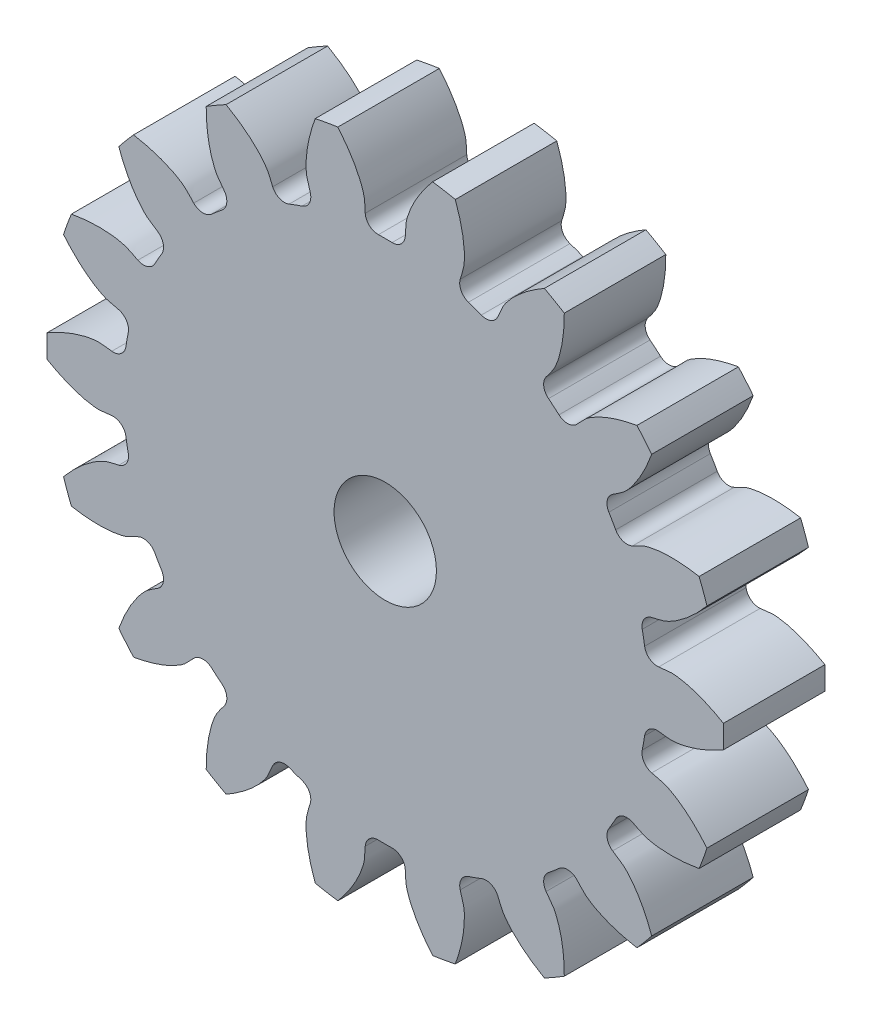
SolidWorks part; units mm, degrees
ref_plane "前视基准面" through (0, 0, 0) normal (0, 0, 1) x (1, 0, 0)
ref_plane "上视基准面" through (0, 0, 0) normal (0, 1, 0) x (1, 0, 0)
ref_plane "右视基准面" through (0, 0, 0) normal (1, 0, 0) x (0, 0, -1)
other "Configuration Table"
ref_axis "Axis1" through (0, 0, -88.99) along (0, 0, 1)
sketch "草图1" plane through (0, 0, 0) normal (0, 0, 1) x (1, 0, 0)
  circle A0 centre (0, 0) radius 20
extrude "LaShenA" add sketch "草图1" along normal blind 6
sketch "SketchA" plane through (0, 0, 6) normal (0, 0, 1) x (1, 0, 0)
  line L0 (0, 0) -> (0, 20) construction
  arc A0 (0.4048, 15.4947) -> (-0.4048, 15.4947) centre (0, 0) ccw
  arc A1 (3.8455, 20.8805) -> (-3.8455, 20.8805) centre (0, 0) ccw
  arc A2 (-0.4048, 15.4947) -> (-1.1828, 16.202) centre (-0.4246, 16.2545) cw
  arc A3 (1.1828, 16.202) -> (0.4048, 15.4947) centre (0.4246, 16.2545) cw
  circle A4 centre (0, 0) radius 16.9145 construction
  circle A5 centre (0, 0) radius 20 construction
  circle A6 centre (0, 0) radius 15.5 construction
  circle A7 centre (0, 0) radius 18 construction
  spline S0 degree 3 poles (1.1828, 16.202) (1.1983, 16.426) (1.1959, 16.7045) (1.2447, 17.0044) (1.2697, 17.1106) (1.2916, 17.1946) (1.3197, 17.2907) (1.3546, 17.3988) (1.3969, 17.5184) (1.4474, 17.6493) (1.5067, 17.791) (1.5754, 17.9431) (1.6542, 18.1053) (1.7437, 18.2771) (1.8445, 18.4579) (1.9572, 18.6473) (2.0823, 18.8448) (2.2203, 19.0498) (2.3718, 19.2616) (2.5373, 19.4798) (2.7172, 19.7037) (2.9119, 19.9326) (3.122, 20.1658) (3.4291, 20.4882) (3.6745, 20.7245) (3.8455, 20.8805) knots 0.120341 0.120341 0.120341 0.120341 0.226675 0.253182 0.264851 0.278642 0.294554 0.312588 0.332744 0.355021 0.37942 0.40594 0.434582 0.465346 0.498232 0.533239 0.570368 0.609618 0.65099 0.694484 0.740099 0.787836 0.837694 0.889675 1 1 1 1
  spline S1 degree 3 poles (-1.1828, 16.202) (-1.1983, 16.426) (-1.1959, 16.7045) (-1.2447, 17.0044) (-1.2697, 17.1106) (-1.2916, 17.1946) (-1.3197, 17.2907) (-1.3546, 17.3988) (-1.3969, 17.5184) (-1.4474, 17.6493) (-1.5067, 17.791) (-1.5754, 17.9431) (-1.6542, 18.1053) (-1.7437, 18.2771) (-1.8445, 18.4579) (-1.9572, 18.6473) (-2.0823, 18.8448) (-2.2203, 19.0498) (-2.3718, 19.2616) (-2.5373, 19.4798) (-2.7172, 19.7037) (-2.9119, 19.9326) (-3.122, 20.1658) (-3.4291, 20.4882) (-3.6745, 20.7245) (-3.8455, 20.8805) knots 0.120341 0.120341 0.120341 0.120341 0.226675 0.253182 0.264851 0.278642 0.294554 0.312588 0.332744 0.355021 0.37942 0.40594 0.434582 0.465346 0.498232 0.533239 0.570368 0.609618 0.65099 0.694484 0.740099 0.787836 0.837694 0.889675 1 1 1 1
  dimension "D1" = 0.76
  dimension "Db" = 33.8289
  dimension "Da" = 40
  dimension "Df" = 31
  dimension "Dn" = 36
extrude "Cut-ExtrudeA" cut sketch "SketchA" against normal blind 30
pattern_circular "www.KYTool.cn" count 18 over 360 about axis through (0, 0, -88.99) along (0, 0, 1) of "Cut-ExtrudeA"
sketch "草图3" plane through (0, 0, 6) normal (0, 0, 1) x (1, 0, 0)
  circle A0 centre (0, 0) radius 3.025
  dimension "D1" = 6.05
extrude "切除-拉伸2" cut sketch "草图3" against normal blind 40
